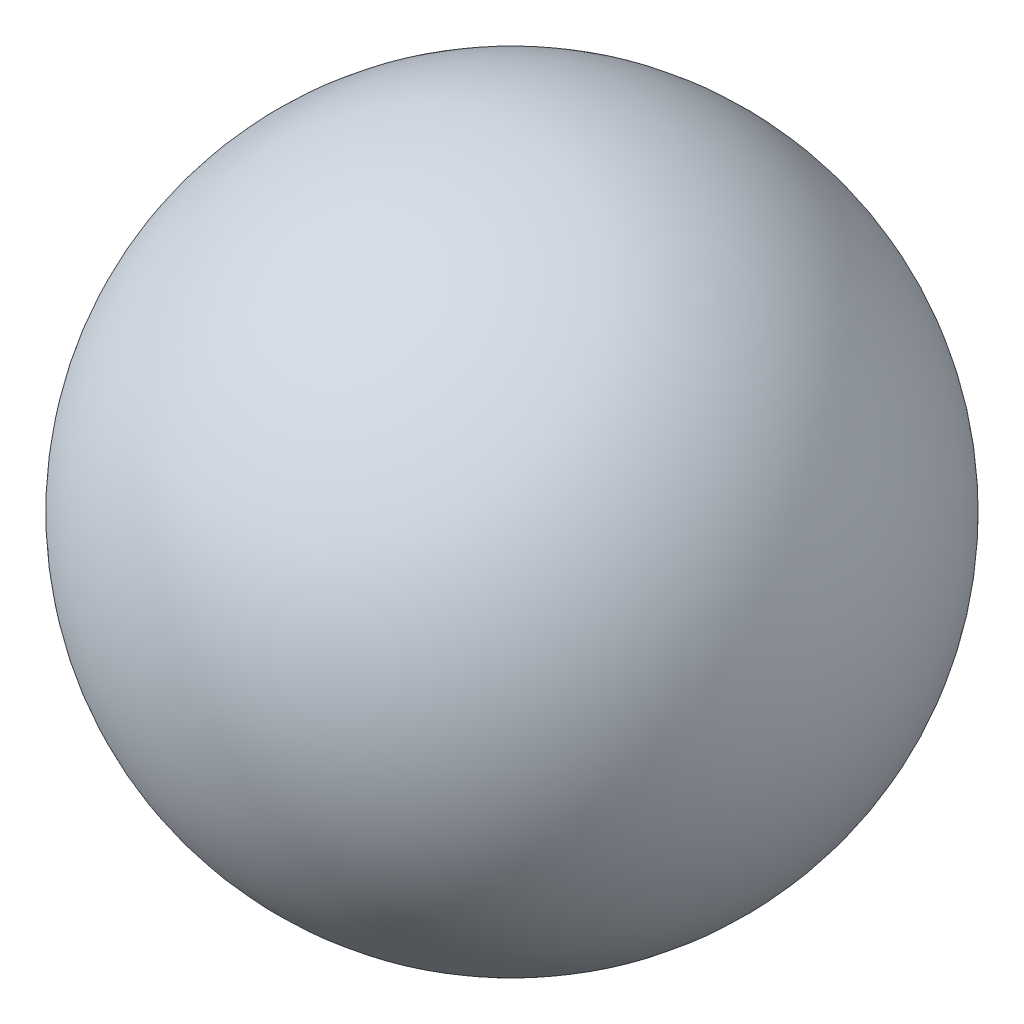
SolidWorks part; units mm, degrees
material "Ti-6Al-4VSolution treated and aged (SS)"
ref_plane "Front Plane" through (0, 0, 0) normal (0, 0, 1) x (1, 0, 0)
ref_plane "Top Plane" through (0, 0, 0) normal (0, 1, 0) x (1, 0, 0)
ref_plane "Right Plane" through (0, 0, 0) normal (1, 0, 0) x (0, 0, -1)
sketch "Sketch1" plane through (0, 0, 0) normal (0, 0, 1) x (1, 0, 0)
  line L0 (0, 303) -> (0, 299)
  line L1 (0, -303) -> (0, -299)
  arc A1 (0, 303) -> (0, -303) centre (0, 0) ccw
  arc A2 (0, 299) -> (0, -299) centre (0, 0) ccw
revolve "Revolve1" add sketch "Sketch1" angle 360 about L1
